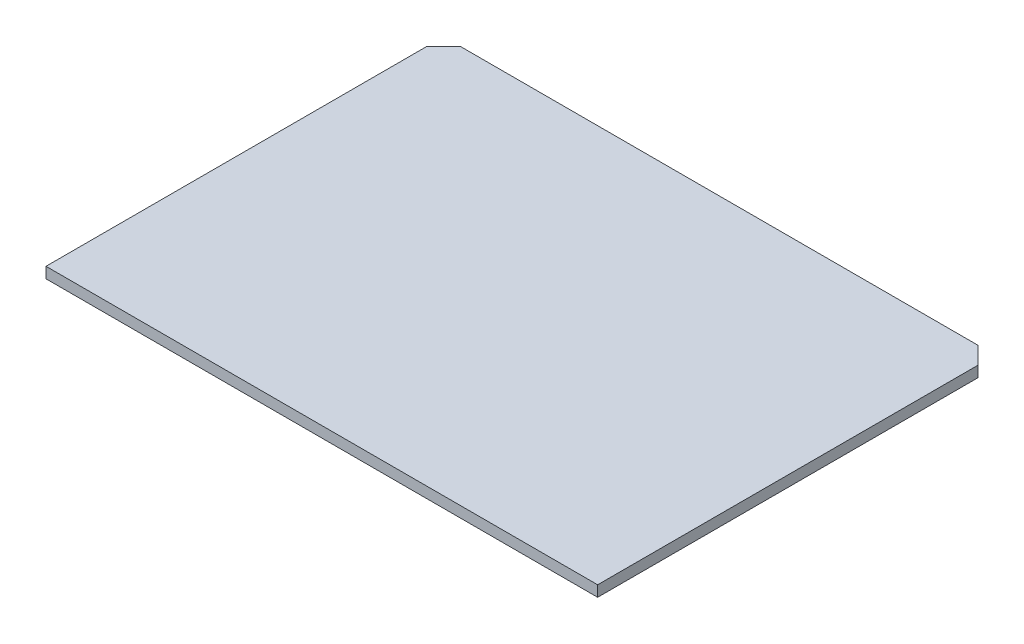
SolidWorks part; units mm, degrees
ref_plane "Front Plane" through (0, 0, 0) normal (0, 0, 1) x (1, 0, 0)
ref_plane "Top Plane" through (0, 0, 0) normal (0, 1, 0) x (1, 0, 0)
ref_plane "Right Plane" through (0, 0, 0) normal (1, 0, 0) x (0, 0, -1)
sketch "Sketch1" plane through (0, 0, 0) normal (0, 1, 0) x (1, 0, 0)
  line L1 (-40.64, 29.29) -> (40.64, 29.29)
  line L2 (-40.64, 29.29) -> (-40.64, -29.29)
  line L3 (-40.64, -29.29) -> (40.64, -29.29)
  line L4 (40.64, 29.29) -> (40.64, -29.29)
  line L5 (-40.64, 29.29) -> (40.64, -29.29) construction
  line L6 (-40.64, -29.29) -> (40.64, 29.29) construction
  point P0 (0, 0)
  dimension "D1" = 81.28
  dimension "D2" = 58.58
extrude "Boss-Extrude1" add sketch "Sketch1" along normal blind 1.6
chamfer "Chamfer1" distance 2.54 angle 45 2 edges at (40.64, 0.8, -29.29) (-40.64, 0.8, -29.29)
